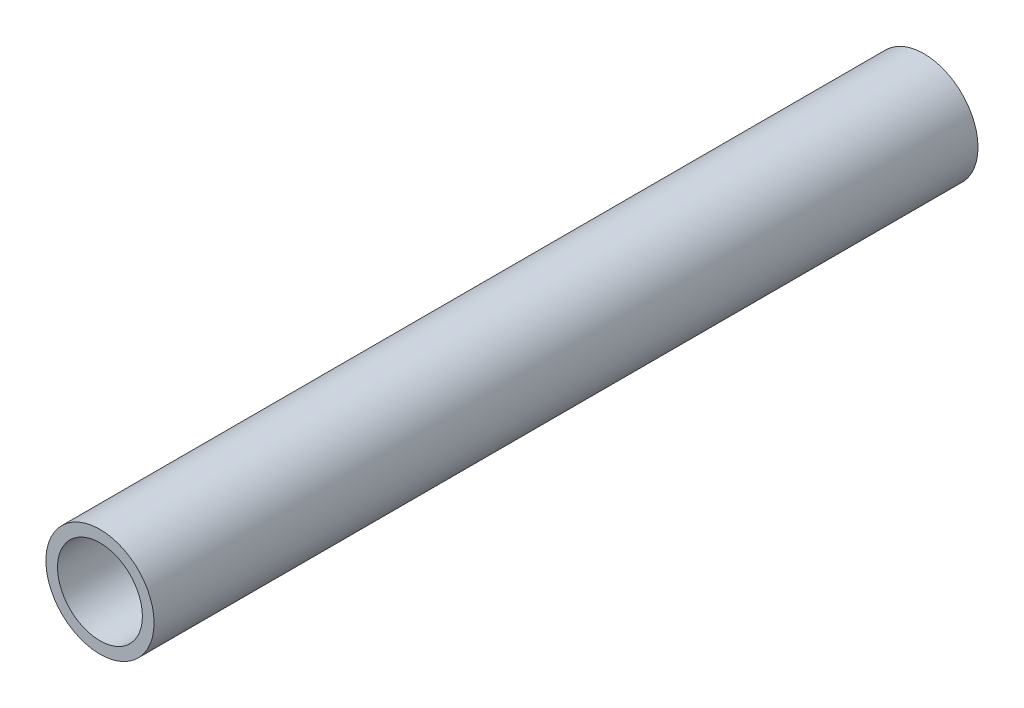
SolidWorks part; units mm, degrees
ref_plane "Front Plane" through (0, 0, 0) normal (0, 0, 1) x (1, 0, 0)
ref_plane "Top Plane" through (0, 0, 0) normal (0, 1, 0) x (1, 0, 0)
ref_plane "Right Plane" through (0, 0, 0) normal (1, 0, 0) x (0, 0, -1)
sketch "Sketch1" plane through (0, 0, 0) normal (0, 0, 1) x (1, 0, 0)
  circle A0 centre (0, 0) radius 10.4648
  circle A1 centre (0, 0) radius 13.335
  dimension "D1" = 2.8702
  dimension "D2" = 26.67
extrude "Boss-Extrude1" add sketch "Sketch1" along normal blind 203.2
